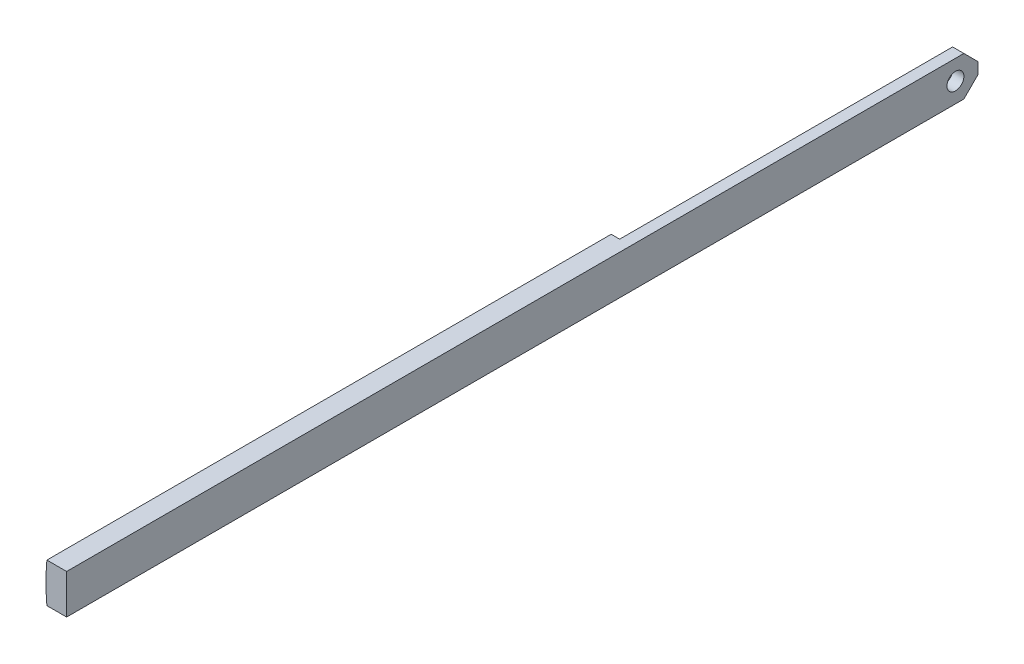
SolidWorks part; units mm, degrees
material "1060-H12"
ref_plane "Plan de face" through (0, 0, 0) normal (0, 0, 1) x (1, 0, 0)
ref_plane "Plan de dessus" through (0, 0, 0) normal (0, 1, 0) x (1, 0, 0)
ref_plane "Plan de droite" through (0, 0, 0) normal (1, 0, 0) x (0, 0, -1)
sketch "Esquisse1" plane through (0, 0, 0) normal (0, 0, 1) x (1, 0, 0)
  line L0 (3, 11.3931) -> (10, 11.3931)
  line L1 (10, 11.3931) -> (10, -2.6069)
  line L2 (10, -2.6069) -> (3, -2.6069)
  arc A0 (3, 11.3931) -> (3, -2.6069) centre (72.6491, 4.3931) ccw
  point P5 (2.6491, 4.3931)
  dimension "D2" = 7
  dimension "D1" = 70
  dimension "D3" = 14
extrude "Boss.-Extru.1" add sketch "Esquisse1" along normal blind 200
sketch "Esquisse2" plane through (0, 0, 0) normal (0, 0, -1) x (-1, 0, 0)
  line L0 (-10, -2.6069) -> (-10, 11.3931) construction
  line L1 (-10, 11.3931) -> (-6, 11.3931)
  line L2 (-10, 11.3931) -> (-10, -2.6069)
  line L3 (-10, -2.6069) -> (-6, -2.6069)
  line L4 (-6, 11.3931) -> (-6, -2.6069)
  line L5 (-10, 11.3931) -> (-3, 11.3931) construction
  line L6 (-3, -2.6069) -> (-10, -2.6069) construction
  dimension "D1" = 4
extrude "Boss.-Extru.2" add sketch "Esquisse2" along normal blind 123
sketch "Esquisse3" plane through (10, 0, 0) normal (1, 0, 0) x (0, 0, -1)
  line L0 (123, 11.3931) -> (123, -2.6069) construction
  line L4 (115, 4.3931) -> (122.4236, 4.3931) construction
  line L5 (-200, 11.3931) -> (123, 11.3931) construction
  line L6 (-200, -2.6069) -> (123, -2.6069) construction
  circle A0 centre (115, 4.3931) radius 3
  dimension "D1" = 6
  dimension "D2" = 8
extrude "Enlèv. mat.-Extru.1" cut sketch "Esquisse3" against normal through all
chamfer "Chanfrein1" distance 5 angle 45 2 edges at (8, -2.6069, -123) (8, 11.3931, -123)
